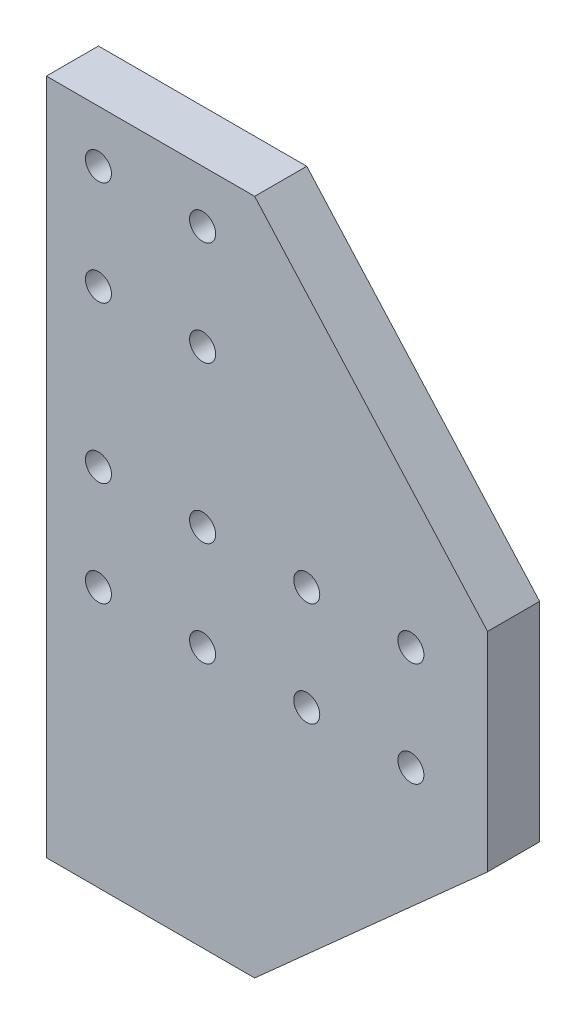
SolidWorks part; units mm, degrees
ref_plane "Front Plane" through (0, 0, 0) normal (0, 0, 1) x (1, 0, 0)
ref_plane "Top Plane" through (0, 0, 0) normal (0, 1, 0) x (1, 0, 0)
ref_plane "Right Plane" through (0, 0, 0) normal (1, 0, 0) x (0, 0, -1)
sketch "Sketch1" plane through (0, 0, 0) normal (0, 0, 1) x (1, 0, 0)
  line L0 (0, 0) -> (40, 0)
  line L1 (40, 0) -> (84.7214, 40)
  line L2 (84.7214, 40) -> (84.7214, 80)
  line L3 (84.7214, 80) -> (40, 130)
  line L4 (40, 130) -> (0, 130)
  line L5 (0, 130) -> (0, 0)
  point P3 (80, 65.6155)
  dimension "D1" = 130
  dimension "D2" = 40
  dimension "D3" = 40
  dimension "D4" = 40
  dimension "D6" = 50
extrude "Boss-Extrude1" add sketch "Sketch1" along normal blind 10
sketch "Sketch2" plane through (0, 0, 10) normal (0, 0, 1) x (1, 0, 0)
  line L0 (40, 130) -> (0, 130) construction
  line L1 (0, 130) -> (0, 0) construction
  circle A0 centre (10, 120) radius 2.5
  circle A1 centre (30, 120) radius 2.5
  circle A2 centre (10, 100) radius 2.5
  circle A3 centre (30, 100) radius 2.5
  circle A4 centre (10, 70) radius 2.5
  circle A5 centre (30, 70) radius 2.5
  circle A6 centre (10, 50) radius 2.5
  circle A7 centre (30, 50) radius 2.5
  circle A8 centre (50, 70) radius 2.5
  circle A9 centre (70, 70) radius 2.5
  circle A10 centre (50, 50) radius 2.5
  circle A11 centre (70, 50) radius 2.5
  point P24 (0, 0)
  point P25 (0, 0)
  point P26 (0, 0)
  point P27 (0, 0)
  point P28 (0, 0)
  point P29 (0, 0)
  point P30 (0, 0)
  point P31 (32.2832, 59.0219)
  point P32 (32.2832, 77.4687)
  point P33 (0, 0)
  point P34 (0, 0)
  dimension "D1" = 5
  dimension "D2" = 10
  dimension "D3" = 10
  dimension "D4" = 20
  dimension "D5" = 20
  dimension "D6" = 30
  dimension "D7" = 20
  dimension "D8" = 20
  dimension "D9" = 20
extrude "Cut-Extrude1" cut sketch "Sketch2" against normal blind 10
